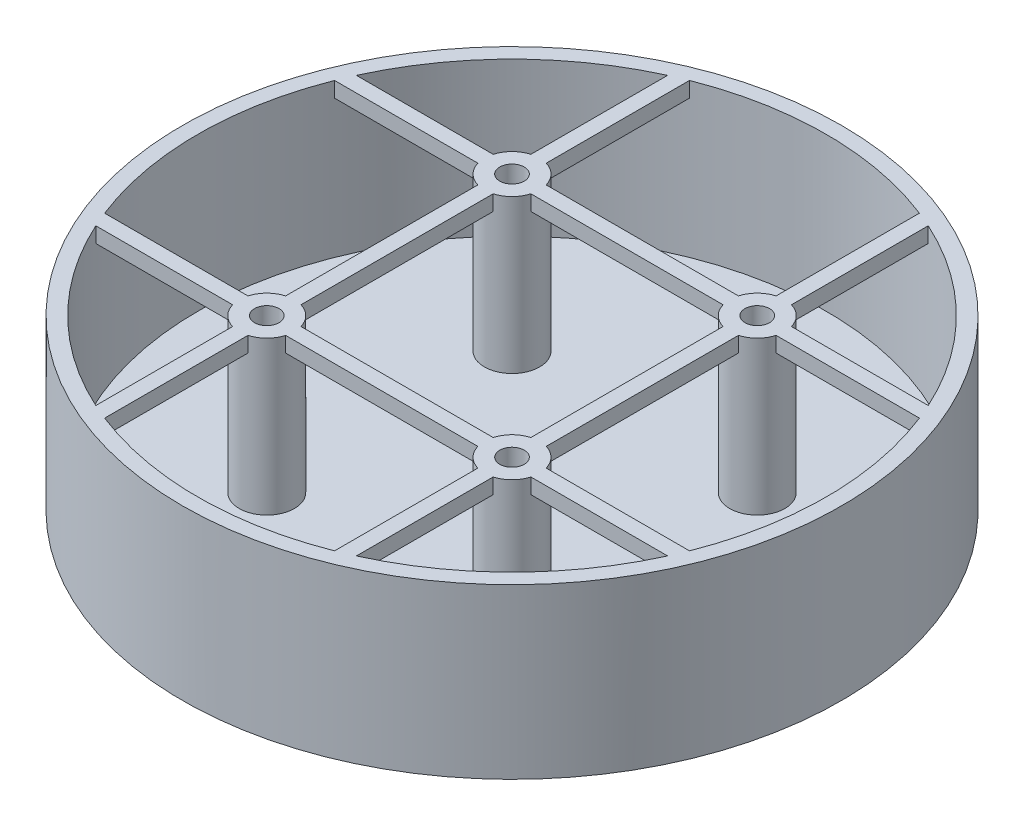
SolidWorks part; units mm, degrees
ref_plane "Front Plane" through (0, 0, 0) normal (0, 0, 1) x (1, 0, 0)
ref_plane "Top Plane" through (0, 0, 0) normal (0, 1, 0) x (1, 0, 0)
ref_plane "Right Plane" through (0, 0, 0) normal (1, 0, 0) x (0, 0, -1)
sketch "Sketch1" plane through (0, 0, 0) normal (0, 1, 0) x (1, 0, 0)
  circle A0 centre (0, 0) radius 53.75
  circle A1 centre (0, 0) radius 51.25
  dimension "D1" = 107.5
  dimension "D2" = 2.5
extrude "Boss-Extrude1" add sketch "Sketch1" along normal blind 25
sketch "Sketch6" plane through (0, 0, 0) normal (0, -1, 0) x (1, 0, 0)
  circle A1 centre (0, 0) radius 53.75
  circle A2 centre (0, 0) radius 53.75
  dimension "D1" = 0
extrude "Boss-Extrude2" add sketch "Sketch6" along normal blind 2.5
sketch "Sketch8" plane through (0, 0, 0) normal (0, 1, 0) x (1, 0, 0)
  line L1 (20, 20) -> (-20, 20) construction
  line L2 (20, 20) -> (20, -20) construction
  line L3 (20, -20) -> (-20, -20) construction
  line L4 (-20, 20) -> (-20, -20) construction
  line L5 (20, 20) -> (-20, -20) construction
  line L6 (20, -20) -> (-20, 20) construction
  circle A0 centre (-20, 20) radius 2
  circle A1 centre (-20, 20) radius 4.5
  circle A2 centre (20, 20) radius 2
  circle A3 centre (20, 20) radius 4.5
  circle A4 centre (20, -20) radius 2
  circle A5 centre (20, -20) radius 4.5
  circle A6 centre (-20, -20) radius 2
  circle A7 centre (-20, -20) radius 4.5
  point P0 (0, 0)
  point P21 (0, 0)
  dimension "D3" = 4
  dimension "D5" = 4
  dimension "D6" = 2.5
  dimension "D7" = 4
  dimension "D8" = 2.5
  dimension "D9" = 4
  dimension "D1" = 40
  dimension "D2" = 40
  dimension "D4" = 2.5
  dimension "D10" = 2.5
extrude "Boss-Extrude3" add sketch "Sketch8" along normal up to surface (25 mm away) up to face at (0, 25, 53.75)
sketch "Sketch12" plane through (0, 25, 0) normal (0, 1, 0) x (1, 0, 0)
  line L0 (-18.75, 18.4388) -> (-18.75, -18.4388)
  line L1 (18.4388, 21.25) -> (-18.4388, 21.25)
  line L2 (21.25, 18.4388) -> (21.25, -18.4388)
  line L3 (18.4388, -21.25) -> (-18.4388, -21.25)
  line L4 (-21.25, 18.4388) -> (-21.25, -18.4388)
  line L5 (18.75, 18.75) -> (-18.5858, -18.5858) construction
  line L6 (21.25, -21.25) -> (-18.5858, 18.5858) construction
  line L7 (18.4388, -18.75) -> (-18.4388, -18.75)
  line L8 (18.75, 18.4388) -> (18.75, -18.4388)
  line L9 (18.4388, 18.75) -> (-18.4388, 18.75)
  line L10 (18.75, 18.75) -> (-18.75, 18.75) construction
  line L11 (-21.5612, 21.25) -> (-49.371, 21.25)
  line L12 (-21.25, 21.5612) -> (-21.25, 49.371)
  line L13 (-18.75, 18.75) -> (-56.0391, 18.75) construction
  line L14 (-21.25, 21.25) -> (-53.5391, 21.25) construction
  line L15 (-21.25, 21.25) -> (-21.25, 51.2303) construction
  line L16 (-18.75, 18.75) -> (-18.75, 53.7303) construction
  line L17 (-21.5612, 18.75) -> (-50.3736, 18.75)
  line L18 (18.75, 21.5612) -> (18.75, 50.3736)
  line L19 (21.5612, 21.25) -> (49.371, 21.25)
  line L20 (21.25, 21.5612) -> (21.25, 49.371)
  line L21 (18.75, -18.75) -> (18.75, -65.0768) construction
  line L22 (21.25, -21.25) -> (21.25, -62.5768) construction
  line L23 (-18.75, -18.75) -> (-58.5391, -18.75) construction
  line L24 (-21.25, -21.25) -> (-56.0391, -21.25) construction
  line L25 (21.5612, 18.75) -> (50.3736, 18.75)
  line L26 (18.75, -21.5612) -> (18.75, -50.3736)
  line L27 (21.5612, -21.25) -> (49.371, -21.25)
  line L28 (21.25, -21.5612) -> (21.25, -49.371)
  line L29 (-18.75, -18.75) -> (-18.75, -65.0768) construction
  line L30 (-21.25, -21.25) -> (-21.25, -62.5768) construction
  line L31 (-21.25, 21.25) -> (-21.25, -21.25) construction
  line L32 (21.25, 21.25) -> (-21.25, 21.25) construction
  line L33 (21.5612, -18.75) -> (50.3736, -18.75)
  line L34 (-18.75, -21.5612) -> (-18.75, -50.3736)
  line L35 (-21.5612, -21.25) -> (-49.371, -21.25)
  line L36 (-21.25, -21.5612) -> (-21.25, -49.371)
  line L37 (21.25, 21.25) -> (21.25, -21.25) construction
  line L38 (18.75, 18.75) -> (18.75, -18.75) construction
  line L39 (21.25, -21.25) -> (-21.25, -21.25) construction
  line L40 (18.75, -18.75) -> (-18.75, -18.75) construction
  line L41 (-21.5612, -18.75) -> (-50.3736, -18.75)
  line L42 (-18.75, 53.7303) -> (-56.0391, 53.7303) construction
  line L43 (-21.25, 51.2303) -> (-53.5391, 51.2303) construction
  line L44 (-53.5391, 21.25) -> (-53.5391, 51.2303) construction
  line L45 (-56.0391, 18.75) -> (-56.0391, 53.7303) construction
  line L46 (18.75, 18.75) -> (18.75, 59.3336) construction
  line L47 (21.25, 21.25) -> (21.25, 56.8336) construction
  line L48 (21.25, 56.8336) -> (55.1885, 56.8336) construction
  line L49 (18.75, 59.3336) -> (57.6885, 59.3336) construction
  line L50 (55.1885, 21.25) -> (55.1885, 56.8336) construction
  line L51 (57.6885, 18.75) -> (57.6885, 59.3336) construction
  line L52 (21.25, 21.25) -> (55.1885, 21.25) construction
  line L53 (18.75, 18.75) -> (57.6885, 18.75) construction
  line L54 (18.75, -18.75) -> (60.1885, -18.75) construction
  line L55 (21.25, -21.25) -> (57.6885, -21.25) construction
  line L56 (57.6885, -21.25) -> (57.6885, -62.5768) construction
  line L57 (60.1885, -18.75) -> (60.1885, -65.0768) construction
  line L58 (21.25, -62.5768) -> (57.6885, -62.5768) construction
  line L59 (18.75, -65.0768) -> (60.1885, -65.0768) construction
  line L60 (-56.0391, -21.25) -> (-56.0391, -62.5768) construction
  line L61 (-58.5391, -18.75) -> (-58.5391, -65.0768) construction
  line L62 (-21.25, -62.5768) -> (-56.0391, -62.5768) construction
  line L63 (-18.75, -65.0768) -> (-58.5391, -65.0768) construction
  line L64 (-18.75, 21.5612) -> (-18.75, 50.3736)
  line L65 (-18.75, 18.75) -> (-18.75, -18.75) construction
  circle A0 centre (-20, 20) radius 2 construction
  arc A1 (-21.5612, 21.25) -> (-21.5612, 18.75) centre (-20, 20) ccw
  circle A2 centre (20, 20) radius 2 construction
  arc A3 (18.75, 18.4388) -> (21.25, 18.4388) centre (20, 20) ccw
  circle A4 centre (20, -20) radius 2 construction
  arc A5 (18.4388, -18.75) -> (18.4388, -21.25) centre (20, -20) ccw
  circle A6 centre (-20, -20) radius 2 construction
  arc A7 (-18.75, -18.4388) -> (-21.25, -18.4388) centre (-20, -20) ccw
  circle A8 centre (0, 0) radius 53.75 construction
  arc A9 (-50.3736, -18.75) -> (-49.371, -21.25) centre (0, 0) ccw
  arc A10 (-18.75, 21.5612) -> (-21.25, 21.5612) centre (-20, 20) ccw
  arc A11 (-21.25, 18.4388) -> (-18.75, 18.4388) centre (-20, 20) ccw
  arc A12 (-18.4388, 18.75) -> (-18.4388, 21.25) centre (-20, 20) ccw
  arc A13 (-49.371, 21.25) -> (-50.3736, 18.75) centre (0, 0) ccw
  arc A14 (-18.75, 50.3736) -> (-21.25, 49.371) centre (0, 0) ccw
  arc A15 (21.25, 49.371) -> (18.75, 50.3736) centre (0, 0) ccw
  arc A16 (50.3736, 18.75) -> (49.371, 21.25) centre (0, 0) ccw
  arc A17 (49.371, -21.25) -> (50.3736, -18.75) centre (0, 0) ccw
  arc A18 (-21.25, -49.371) -> (-18.75, -50.3736) centre (0, 0) ccw
  arc A19 (18.75, -50.3736) -> (21.25, -49.371) centre (0, 0) ccw
  arc A20 (18.4388, 21.25) -> (18.4388, 18.75) centre (20, 20) ccw
  arc A21 (21.25, 21.5612) -> (18.75, 21.5612) centre (20, 20) ccw
  arc A22 (21.5612, 18.75) -> (21.5612, 21.25) centre (20, 20) ccw
  arc A23 (21.25, -18.4388) -> (18.75, -18.4388) centre (20, -20) ccw
  arc A24 (21.5612, -21.25) -> (21.5612, -18.75) centre (20, -20) ccw
  arc A25 (18.75, -21.5612) -> (21.25, -21.5612) centre (20, -20) ccw
  arc A26 (-21.5612, -18.75) -> (-21.5612, -21.25) centre (-20, -20) ccw
  arc A27 (-21.25, -21.5612) -> (-18.75, -21.5612) centre (-20, -20) ccw
  arc A28 (-18.4388, -21.25) -> (-18.4388, -18.75) centre (-20, -20) ccw
  point P0 (0, 0)
  dimension "D4" = 2.5
  dimension "D9" = 2.5
  dimension "D3" = 2.5
  dimension "D12" = 2.5
  dimension "D15" = 2.5
extrude "Boss-Extrude4" add sketch "Sketch12" against normal blind 2.5
